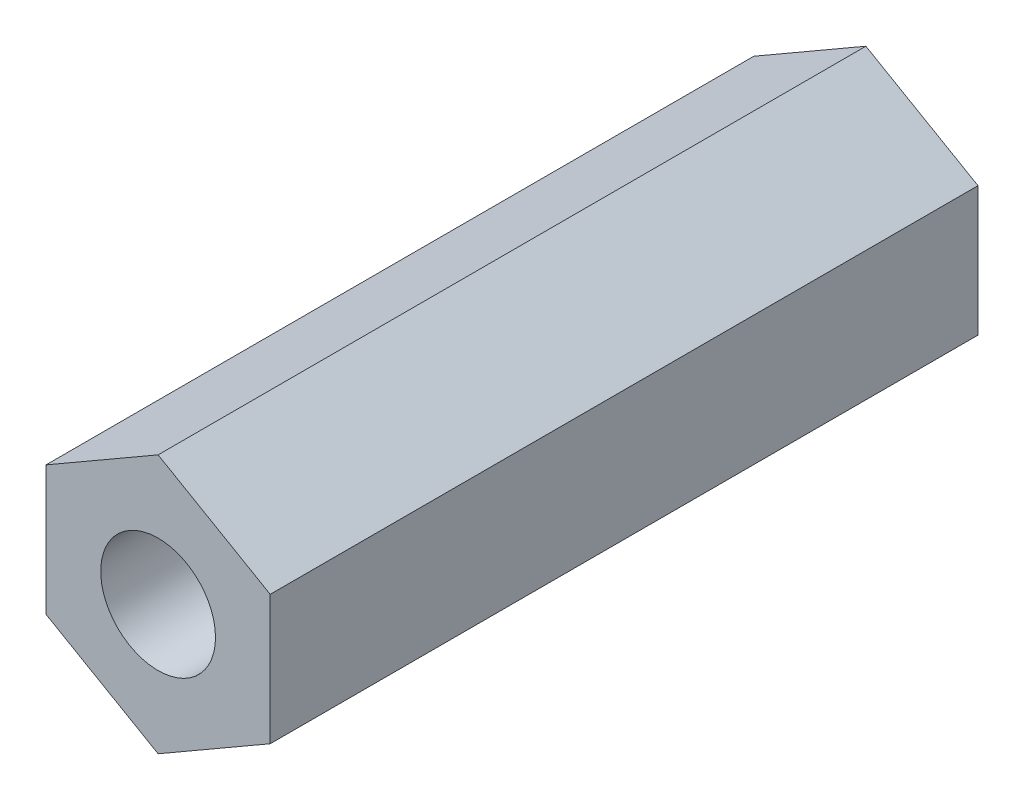
SolidWorks part; units mm, degrees
ref_plane "Plan de face" through (0, 0, 0) normal (0, 0, 1) x (1, 0, 0)
ref_plane "Plan de dessus" through (0, 0, 0) normal (0, 1, 0) x (1, 0, 0)
ref_plane "Plan de droite" through (0, 0, 0) normal (1, 0, 0) x (0, 0, -1)
sketch "Esquisse1" plane through (0, 0, 0) normal (0, 0, 1) x (1, 0, 0)
  line L1 (0, -3.3833) -> (2.93, -1.6916)
  line L2 (2.93, -1.6916) -> (2.93, 1.6916)
  line L3 (2.93, 1.6916) -> (0, 3.3833)
  line L4 (0, 3.3833) -> (-2.93, 1.6916)
  line L5 (-2.93, 1.6916) -> (-2.93, -1.6916)
  line L6 (-2.93, -1.6916) -> (0, -3.3833)
  circle A0 centre (0, 0) radius 1.5
  circle A1 centre (0, 0) radius 2.93 construction
  dimension "D1" = 3
  dimension "D2" = 5.86
extrude "Boss.-Extru.1" add sketch "Esquisse1" along normal blind 18.5
